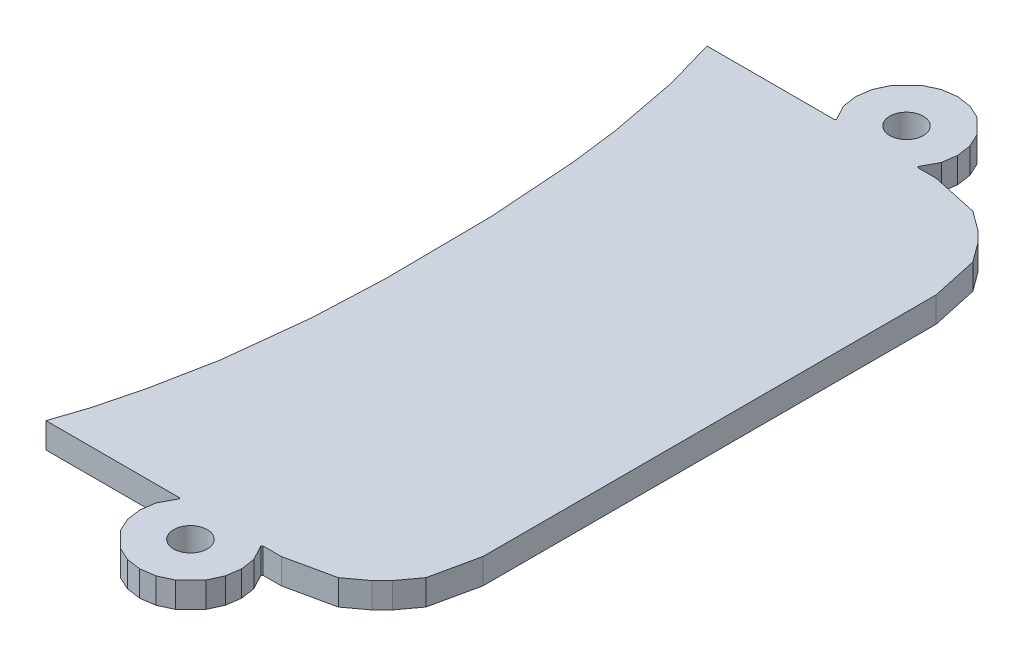
SolidWorks part; units mm, degrees
ref_plane "Front Plane" through (0, 0, 0) normal (0, 0, 1) x (1, 0, 0)
ref_plane "Top Plane" through (0, 0, 0) normal (0, 1, 0) x (1, 0, 0)
ref_plane "Right Plane" through (0, 0, 0) normal (1, 0, 0) x (0, 0, -1)
ref_plane "P1_Top_28" through (0, 28, 0) normal (0, 1, 0) x (1, 0, 0)
sketch "Sketch1" plane through (0, 28, 0) normal (0, 1, 0) x (1, 0, 0)
  line L0 (86.3, 45.2) -> (84.9, 45)
  line L1 (84.9, 45) -> (83.6, 44.4)
  line L2 (83.6, 44.4) -> (82.1, 42.9)
  line L3 (82.1, 42.9) -> (81.5, 41.6)
  line L4 (81.5, 41.6) -> (81.3, 40.2)
  line L5 (81.3, 40.2) -> (81.5, 38.8)
  line L6 (81.5, 38.8) -> (82.3, 37.3)
  line L7 (82.3, 37.3) -> (82.2, 37.2)
  line L8 (82.2, 37.2) -> (69.7, 37.2)
  line L9 (69.7, 37.2) -> (71.1, 32.3)
  line L10 (71.1, 32.3) -> (72.4, 25.5)
  line L11 (72.4, 25.5) -> (73, 20.7)
  line L12 (73, 20.7) -> (73.6, 12.1)
  line L13 (73.6, 12.1) -> (73.7, 1.7)
  line L14 (73.7, 1.7) -> (73.4, -5.3)
  line L15 (73.4, -5.3) -> (72.5, -13.4)
  line L16 (72.5, -13.4) -> (71.3, -19.5)
  line L17 (71.3, -19.5) -> (70.2, -23.8)
  line L18 (70.2, -23.8) -> (69.1, -27.1)
  line L19 (69.1, -27.1) -> (82.2, -27.1)
  line L20 (82.2, -27.1) -> (82.3, -27.2)
  line L21 (82.3, -27.2) -> (81.5, -28.7)
  line L22 (81.5, -28.7) -> (81.3, -30.1)
  line L23 (81.3, -30.1) -> (81.5, -31.5)
  line L24 (81.5, -31.5) -> (82.1, -32.8)
  line L25 (82.1, -32.8) -> (83.6, -34.3)
  line L26 (83.6, -34.3) -> (84.9, -34.9)
  line L27 (84.9, -34.9) -> (86.3, -35.1)
  line L28 (86.3, -35.1) -> (87.7, -34.9)
  line L29 (87.7, -34.9) -> (89, -34.3)
  line L30 (89, -34.3) -> (90.5, -32.8)
  line L31 (90.5, -32.8) -> (91.1, -31.5)
  line L32 (91.1, -31.5) -> (91.3, -30.1)
  line L33 (91.3, -30.1) -> (91.1, -28.7)
  line L34 (91.1, -28.7) -> (90.3, -27.2)
  line L35 (90.3, -27.2) -> (90.4, -27.1)
  line L36 (90.4, -27.1) -> (92.2, -27.1)
  line L37 (92.2, -27.1) -> (96.8, -26.1)
  line L38 (96.8, -26.1) -> (98.7, -24.7)
  line L39 (98.7, -24.7) -> (99.7, -23.7)
  line L40 (99.7, -23.7) -> (101.1, -21.8)
  line L41 (101.1, -21.8) -> (102.1, -17.2)
  line L42 (102.1, -17.2) -> (102.1, 27.3)
  line L43 (102.1, 27.3) -> (101.1, 31.9)
  line L44 (101.1, 31.9) -> (99.7, 33.8)
  line L45 (99.7, 33.8) -> (98.7, 34.8)
  line L46 (98.7, 34.8) -> (96.8, 36.2)
  line L47 (96.8, 36.2) -> (92.2, 37.2)
  line L48 (92.2, 37.2) -> (90.4, 37.2)
  line L49 (90.4, 37.2) -> (90.3, 37.3)
  line L50 (90.3, 37.3) -> (91.1, 38.8)
  line L51 (91.1, 38.8) -> (91.3, 40.2)
  line L52 (91.3, 40.2) -> (91.1, 41.6)
  line L53 (91.1, 41.6) -> (90.5, 42.9)
  line L54 (90.5, 42.9) -> (89, 44.4)
  line L55 (89, 44.4) -> (87.7, 45)
  line L56 (87.7, 45) -> (86.3, 45.2)
extrude "Pedal cover" add sketch "Sketch1" along normal blind 2.5
ref_plane "P2_Top_28" through (0, 28, 0) normal (0, 1, 0) x (1, 0, 0)
sketch "Sketch2" plane through (0, 28, 0) normal (0, 1, 0) x (1, 0, 0)
  circle A0 centre (86.28, 40.2) radius 1.65
  circle A1 centre (86.28, -30.1) radius 1.65
extrude "Cover screw holes" cut sketch "Sketch2" along normal through all
